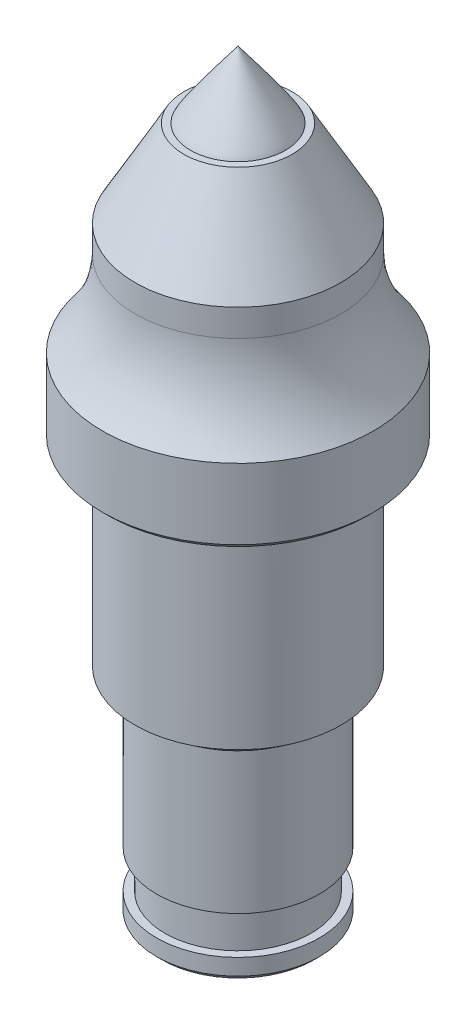
SolidWorks part; units mm, degrees
ref_plane "Plan de face" through (0, 0, 0) normal (0, 0, 1) x (1, 0, 0)
ref_plane "Plan de dessus" through (0, 0, 0) normal (0, 1, 0) x (1, 0, 0)
ref_plane "Plan de droite" through (0, 0, 0) normal (1, 0, 0) x (0, 0, -1)
sketch "Esquisse1" plane through (0, 0, 0) normal (0, 0, 1) x (1, 0, 0)
  line L0 (0, 65.9448) -> (0, -73.0552) construction
  line L1 (0, -73.0552) -> (-15, -73.0552)
  line L2 (-15, -73.0552) -> (-15, -69.0552)
  line L3 (-15, -69.0552) -> (-13.5, -69.0552)
  line L4 (-13.5, -69.0552) -> (-13.5, -62.0552)
  line L5 (-13.5, -62.0552) -> (-15, -62.0552)
  line L6 (-15, -62.0552) -> (-15, -36.0552)
  line L7 (-19, 2.9448) -> (-25, 2.9448)
  line L8 (-15, -36.0552) -> (-19, -33.0552)
  line L9 (-25, 2.9448) -> (-25, 16.9448)
  line L10 (-19, -33.0552) -> (-19, 2.9448)
  line L11 (-19, 32.6426) -> (-19, 37.6426)
  line L12 (-19, 37.6426) -> (-10, 53.6426)
  line L13 (-10, 53.6426) -> (-8.75, 53.6426)
  line L14 (0, 65.9448) -> (0, -73.0552)
  spline S0 degree 2 poles (-25, 16.9448) (-19.2446, 23.9822) (-19, 32.6426) knots 0 0 0 1 1 1
  spline S1 degree 2 poles (-8.75, 53.6426) (-8.0466, 55.3071) (0, 65.9448) knots 0 0 0 1 1 1
  point P6 (0, 70.5278)
  point P8 (0, 65.9448)
  point P16 (-19.5342, 28.0824)
  dimension "D1" = 139
  dimension "D2" = 4
  dimension "D3" = 7
  dimension "D4" = 26
  dimension "D5" = 15
  dimension "D6" = 13.5
  dimension "D7" = 15
  dimension "D8" = 3
  dimension "D9" = 36
  dimension "D10" = 19
  dimension "D11" = 14
  dimension "D12" = 25
  dimension "D13" = 5
  dimension "D14" = 16
  dimension "D15" = 17.5
  dimension "D16" = 20
  dimension "D17" = 38
revolve "Révolution1" add sketch "Esquisse1" angle 360 about L0
chamfer "Chanfrein1" distance 1 angle 45 1 edges at (-25, 2.9448, 0)
fillet "Congé1" radius 2 1 edges at (-19, 2.9448, 0)
chamfer "Chanfrein2" distance 1 angle 45 1 edges at (-15, -73.0552, 0)
